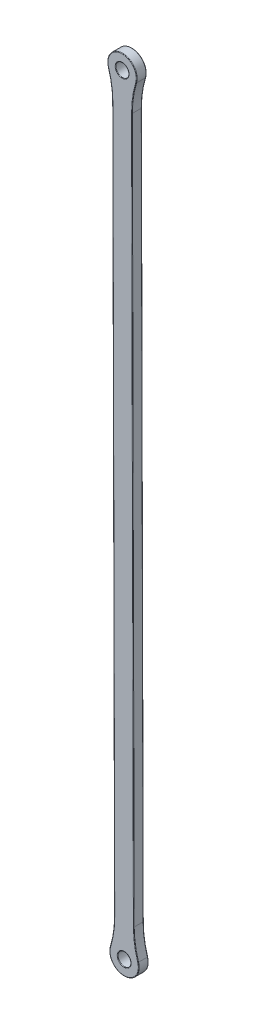
SolidWorks part; units mm, degrees
ref_plane "Front Plane" through (0, 0, 0) normal (0, 0, 1) x (1, 0, 0)
ref_plane "Top Plane" through (0, 0, 0) normal (0, 1, 0) x (1, 0, 0)
ref_plane "Right Plane" through (0, 0, 0) normal (1, 0, 0) x (0, 0, -1)
sketch "Sketch1" plane through (0, 0, 0) normal (0, 0, 1) x (1, 0, 0)
  line L1 (14.5, -7.3005) -> (13.872, 229.4995) construction
  line L2 (14.5, -7.3005) -> (13.872, 229.4995) construction
  line L3 (11.4911, -3.9544) -> (10.8809, 226.1374)
  line L4 (17.4911, -3.9385) -> (16.8809, 226.1533)
  arc A0 (16.8809, 226.1533) -> (10.8809, 226.1374) centre (13.872, 229.4995) ccw
  arc A1 (11.4911, -3.9544) -> (17.4911, -3.9385) centre (14.5, -7.3005) ccw
  circle A4 centre (13.872, 229.4995) radius 2
  circle A5 centre (14.5, -7.3005) radius 2
  arc A6 (10.8809, 226.1374) -> (16.8809, 226.1533) centre (13.872, 229.4995) cw
  arc A7 (17.4911, -3.9385) -> (11.4911, -3.9544) centre (14.5, -7.3005) cw
  point P5 (14.186, 111.0995)
  dimension "D1" = 9
  dimension "D2" = 9
  dimension "D5" = 4
  dimension "D6" = 4
  dimension "D3" = 6
  dimension "D4" = 236.8
extrude "Boss-Extrude1" add sketch "Sketch1" against normal blind 3
fillet "Fillet1" radius 30 4 edges at (17.4911, -3.9385, -1.5) (11.4911, -3.9544, -1.5) (10.8809, 226.1374, -1.5) (16.8809, 226.1533, -1.5)
fillet "Fillet2" radius 0.15 20 edges at (10.5591, 223.8516, -3) (10.5591, 223.8516, 0) (13.8601, 233.9995, -3) (13.8601, 233.9995, 0) (17.2148, 223.8693, -3) (17.2148, 223.8693, 0) (17.186, 111.1074, 0) (17.186, 111.1074, -3) (17.8129, -1.6527, -3) (17.8129, -1.6527, 0) (14.5119, -11.8005, -3) (14.5119, -11.8005, 0) (11.1572, -1.6703, -3) (11.1572, -1.6703, 0) (11.186, 111.0915, -3) (11.186, 111.0915, 0) (15.872, 229.4995, -3) (15.872, 229.4995, 0) (16.5, -7.3005, -3) (16.5, -7.3005, 0)
